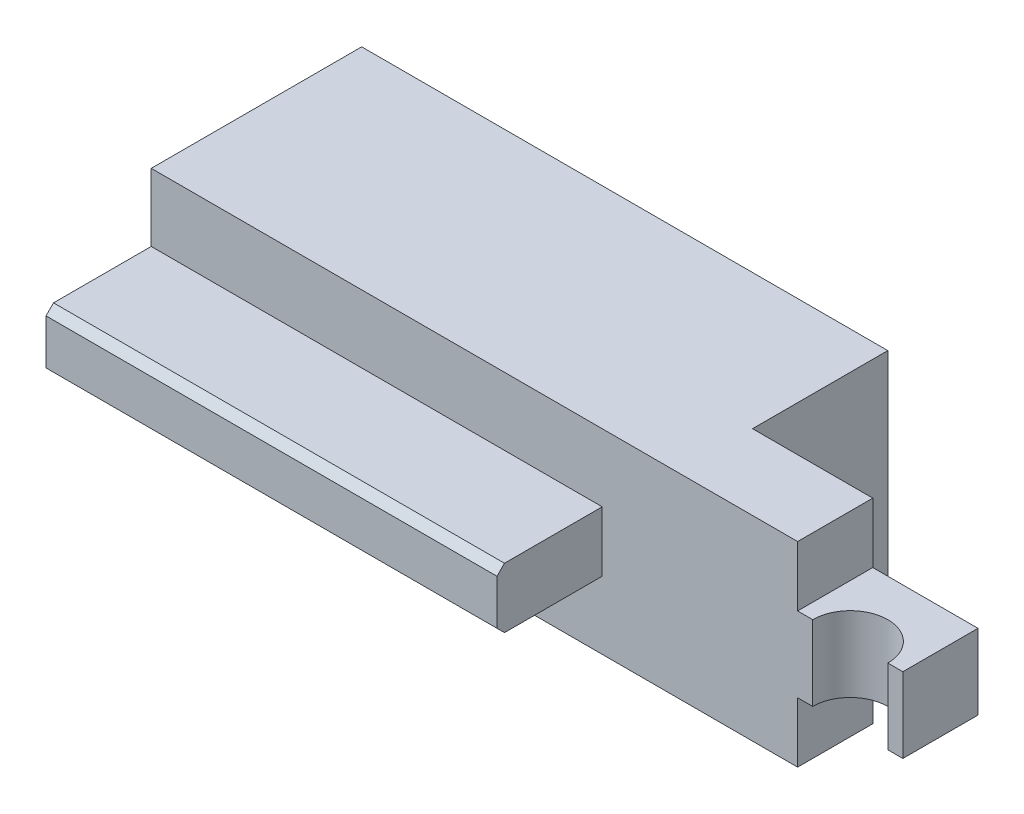
SolidWorks part; units mm, degrees
ref_plane "前视基准面" through (0, 0, 0) normal (0, 0, 1) x (1, 0, 0)
ref_plane "上视基准面" through (0, 0, 0) normal (0, 1, 0) x (1, 0, 0)
ref_plane "右视基准面" through (0, 0, 0) normal (1, 0, 0) x (0, 0, -1)
sketch "草图1" plane through (0, 0, 0) normal (1, 0, 0) x (0, 0, -1)
  line L0 (-15.5739, 0) -> (17.5206, 0) construction
  line L1 (0, 0) -> (0, 24.6123) construction
  line L2 (0, 0) -> (25, 0)
  line L3 (25, 0) -> (25, 17)
  line L4 (25, 17) -> (0, 17)
  line L5 (0, 17) -> (0, 0)
extrude "凸台-拉伸1" add sketch "草图1" along normal blind 50
sketch "草图2" plane through (0, 0, 0) normal (-1, 0, 0) x (0, 0, 1)
  line L0 (0, 17) -> (0, 11)
  line L1 (0, 17) -> (0, 0) construction
  line L2 (0, 11) -> (-11, 11)
  line L3 (-11, 11) -> (-11, 17)
  line L4 (-25, 17) -> (0, 17) construction
  line L5 (-11, 17) -> (0, 17)
  line L6 (-25, 8.5) -> (0, 8.5) construction
  line L7 (-25, 0) -> (-25, 17) construction
  line L8 (-11, 6) -> (-11, 0)
  line L9 (0, 6) -> (-11, 6)
  line L10 (0, 0) -> (0, 6)
  line L11 (-11, 0) -> (0, 0)
extrude "切除-拉伸1" cut sketch "草图2" against normal blind 50 contours L5 L0 L2 L3 | L8 L11 L10 L9
sketch "草图3" plane through (0, 11, 0) normal (0, 1, 0) x (1, 0, 0)
  line L0 (50, 0) -> (50, 11)
  line L1 (50, 11) -> (30, 11)
  line L2 (50, 11) -> (0, 11) construction
  line L3 (30, 11) -> (30, 0)
  line L4 (50, 0) -> (0, 0) construction
  line L5 (30, 0) -> (50, 0)
extrude "切除-拉伸2" cut sketch "草图3" against normal blind 50
sketch "草图4" plane through (0, 0, -25) normal (0, 0, -1) x (-1, 0, 0)
  line L0 (-50, 8.5) -> (0, 8.5) construction
  line L1 (-50, 0) -> (-50, 17) construction
  line L2 (0, 0) -> (0, 17) construction
  line L4 (-50, 11) -> (-43, 11)
  line L5 (-43, 11) -> (-43, 17)
  line L6 (-50, 17) -> (0, 17) construction
  line L7 (-43, 17) -> (-50, 17)
  line L8 (-50, 17) -> (-50, 11)
  line L9 (-50, 0) -> (-50, 6)
  line L10 (-43, 0) -> (-50, 0)
  line L11 (-43, 6) -> (-43, 0)
  line L12 (-50, 6) -> (-43, 6)
extrude "切除-拉伸3" cut sketch "草图4" against normal blind 50
sketch "草图5" plane through (0, 11, 0) normal (0, 1, 0) x (1, 0, 0)
  line L1 (50, 11) -> (50, 25) construction
  line L2 (50, 16) -> (43, 16)
  line L3 (43, 11) -> (43, 25) construction
  line L4 (43, 16) -> (43, 25)
  line L5 (43, 25) -> (50, 25)
  line L6 (50, 25) -> (50, 16)
extrude "切除-拉伸4" cut sketch "草图5" against normal blind 50 contours L2 L4 L5 L6
sketch "草图6" plane through (0, 11, 0) normal (0, 1, 0) x (1, 0, 0)
  line L0 (43, 11) -> (50, 11) construction
  circle A0 centre (46.5, 11) radius 2.5
extrude "切除-拉伸5" cut sketch "草图6" against normal blind 50
sketch "草图7" plane through (0, 0, 0) normal (-1, 0, 0) x (0, 0, 1)
  line L0 (0, 8.5) -> (-25, 8.5)
  line L1 (0, 11) -> (0, 6) construction
  line L2 (-25, 0) -> (-25, 17) construction
  line L3 (-25, 17) -> (-25, 15)
  line L4 (-25, 15) -> (-11, 15)
  line L5 (-11, 11) -> (-11, 17) construction
  line L6 (-11, 15) -> (-11, 17)
  line L7 (-11, 17) -> (-25, 17)
  line L8 (-11, 2) -> (-11, 0)
  line L9 (-25, 2) -> (-11, 2)
  line L10 (-25, 0) -> (-25, 2)
  line L11 (-11, 0) -> (-25, 0)
  line M6 (-11, 11) -> (-11, 17)
  line M7 (-11, 17) -> (-25, 17)
  line M8 (-25, 17) -> (-25, 0)
  line M9 (-25, 0) -> (-11, 0)
  line M10 (-11, 0) -> (-11, 6)
extrude "切除-拉伸8" cut sketch "草图7" against normal blind 50 contours L4 M8 M6 M7 | L9 M8 M9 M10
sketch "草图10" plane through (0, 0, 0) normal (-1, 0, 0) x (0, 0, 1)
  line L0 (0, 11) -> (-4, 11)
  line L1 (0, 11) -> (-11, 11) construction
  line L2 (-4, 11) -> (-4, 6)
  line L3 (0, 6) -> (-11, 6) construction
  line L4 (-4, 6) -> (0, 6)
  line L5 (0, 6) -> (0, 11)
extrude "切除-拉伸9" cut sketch "草图10" against normal blind 50
sketch "草图11" plane through (0, 0, 0) normal (-1, 0, 0) x (0, 0, 1)
  line L0 (-22, 12) -> (-22, 5)
  line L3 (-22, 12) -> (-14, 12)
  line L4 (-14, 12) -> (-14, 5)
  line L5 (-14, 5) -> (-22, 5)
extrude "切除-拉伸10" cut sketch "草图11" against normal blind 30
sketch "草图12" plane through (0, 0, 0) normal (-1, 0, 0) x (0, 0, 1)
  line L0 (-4, 8.5) -> (-25, 8.5) construction
  line L1 (-4, 11) -> (-4, 6) construction
  line L2 (-25, 2) -> (-25, 15) construction
  line L3 (-4, 11) -> (-4, 10)
  line L4 (-4, 11) -> (-5, 11)
  line L5 (-4, 11) -> (-11, 11) construction
  line L6 (-5, 11) -> (-4, 10)
  line L7 (-4, 6) -> (-5, 6)
  line L8 (-4, 6) -> (-4, 7)
  line L9 (-5, 6) -> (-4, 7)
extrude "切除-拉伸11" cut sketch "草图12" against normal blind 50 contours L6 L3 L4 | L7 L9 L8
sketch "草图13" plane through (0, 0, 0) normal (-1, 0, 0) x (0, 0, 1)
  line L0 (-11, 11) -> (-11, 10.5)
  line L1 (-11, 10.5) -> (-4.5, 10.5)
  line L2 (-5, 11) -> (-4, 10) construction
  line L3 (-4.5, 10.5) -> (-5, 11)
  line L4 (-5, 11) -> (-11, 11)
  line L5 (-4, 8.5) -> (-25, 8.5) construction
  line L6 (-4, 10) -> (-4, 7) construction
  line L7 (-25, 2) -> (-25, 15) construction
  line L8 (-4.5, 6.5) -> (-5, 6)
  line L9 (-11, 6.5) -> (-4.5, 6.5)
  line L10 (-11, 6) -> (-11, 6.5)
  line L11 (-5, 6) -> (-11, 6)
extrude "切除-拉伸12" cut sketch "草图13" against normal blind 50
sketch "草图14" plane through (0, 0, -25) normal (0, 0, -1) x (-1, 0, 0)
  circle A0 centre (-3, 8.5) radius 1.55
  circle A1 centre (-11, 8.5) radius 1.55
extrude "切除-拉伸13" cut sketch "草图14" against normal blind 5 contours A0 | A1
sketch "Skizze1" plane through (43, 0, 0) normal (1, 0, 0) x (0, 0, -1)
  line L1 (25, 15) -> (11, 15) construction
  line L5 (25, 2) -> (11, 2) construction
  line L7 (16, 15) -> (16, 2)
  line L9 (16, 15) -> (25, 15)
  line L10 (25, 15) -> (25, 2)
  line L11 (25, 2) -> (16, 2)
extrude "Schnitt-Linear austragen1" cut sketch "Skizze1" against normal blind 8
